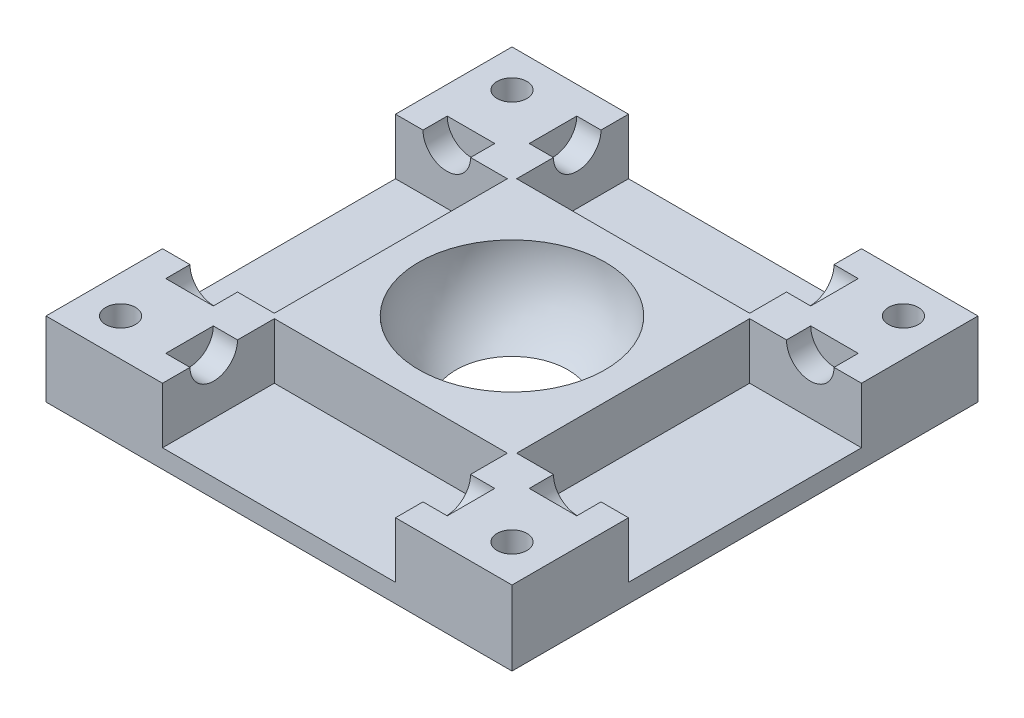
SolidWorks part; units mm, degrees
ref_plane "前视基准面" through (0, 0, 0) normal (0, 0, 1) x (1, 0, 0)
ref_plane "上视基准面" through (0, 0, 0) normal (0, 1, 0) x (1, 0, 0)
ref_plane "右视基准面" through (0, 0, 0) normal (1, 0, 0) x (0, 0, -1)
sketch "草图1" plane through (0, 0, 0) normal (0, 1, 0) x (1, 0, 0)
  line L1 (-25, -25) -> (25, -25)
  line L2 (-25, -25) -> (-25, 25)
  line L3 (-25, 25) -> (25, 25)
  line L4 (25, -25) -> (25, 25)
  line L5 (-25, -25) -> (25, 25) construction
  line L6 (-25, 25) -> (25, -25) construction
  point P0 (0, 0)
  dimension "D1" = 50
  dimension "D2" = 50
extrude "凸台-拉伸1" add sketch "草图1" along normal blind 16
sketch "草图2" plane through (0, 0, 0) normal (0, 0, 1) x (1, 0, 0)
  line L0 (0, 16) -> (0, 0) construction
  line L2 (0, 18) -> (0, -2)
  line L3 (-25, 8) -> (25, 8) construction
  line L4 (-25, 16) -> (-25, 0) construction
  line L5 (25, 16) -> (25, 0) construction
  circle A0 centre (0, 8) radius 10 construction
  arc A1 (0, 18) -> (0, -2) centre (0, 8) cw
  dimension "D1" = 20
revolve "切除-旋转1" cut sketch "草图2" angle 360 about L0
sketch "草图3" plane through (0, 16, 0) normal (0, 1, 0) x (1, 0, 0)
  line L0 (-25, 25) -> (-25, -25) construction
  line L1 (-21, -21) -> (21, -21) construction
  line L2 (-21, -21) -> (-21, 21) construction
  line L3 (-21, 21) -> (21, 21) construction
  line L4 (21, -21) -> (21, 21) construction
  line L5 (-21, -21) -> (21, 21) construction
  line L6 (-21, 21) -> (21, -21) construction
  line L7 (25, 25) -> (-25, 25) construction
  circle A0 centre (-21, 21) radius 1.6
  circle A1 centre (21, 21) radius 1.6
  circle A2 centre (21, -21) radius 1.6
  circle A3 centre (-21, -21) radius 1.6
  point P0 (0, 0)
  point P20 (0, 0)
  dimension "D3" = 3.2
  dimension "D1" = 4
  dimension "D2" = 4
  dimension "D4" = 4
extrude "切除-拉伸1" cut sketch "草图3" against normal through all
sketch "草图4" plane through (0, 16, 0) normal (0, 1, 0) x (1, 0, 0)
  circle A0 centre (-21, 21) radius 3
  dimension "D1" = 6
extrude "切除-拉伸2" [suppressed] cut sketch "草图4" against normal blind 3
sketch "草图5" plane through (0, 0, 0) normal (0, 0, 1) x (1, 0, 0)
  line L0 (0, 16) -> (0, 0) construction
  line L1 (-25, 16) -> (25, 16) construction
pattern_circular "阵列(圆周)1" [suppressed] count 4 over 360 about axis through (0, 16, 0) along (0, -1, 0)
ref_plane "基准面1" through (0, 8, 0) normal (0, 1, 0) x (1, 0, 0)
mirror "镜向1" [suppressed] about plane through (0, 8, 0) normal (0, 1, 0)
sketch "草图6" plane through (0, 0, 25) normal (0, 0, 1) x (1, 0, 0)
  line L0 (0, 16) -> (0, 0) construction
  line L1 (-12.5, 2) -> (12.5, 2)
  line L2 (-12.5, 2) -> (-12.5, 14)
  line L3 (-12.5, 14) -> (12.5, 14)
  line L4 (12.5, 2) -> (12.5, 14)
  line L5 (-12.5, 2) -> (12.5, 14) construction
  line L6 (-12.5, 14) -> (12.5, 2) construction
  point P0 (0, 8)
  dimension "D1" = 25
  dimension "D2" = 12
extrude "切除-拉伸3" cut sketch "草图6" against normal blind 12
sketch "草图7" plane through (0, 0, 0) normal (1, 0, 0) x (0, 0, -1)
  line L0 (-25, 8) -> (25, 8) construction
  line L1 (-25, 16) -> (-25, 0) construction
  line L2 (25, 16) -> (25, 0) construction
  line L3 (0, 16) -> (0, 0) construction
  line L4 (-25, 16) -> (25, 16) construction
  circle A0 centre (-19.5, 8) radius 2.55
  dimension "D1" = 5.1
  dimension "D2" = 5.5
extrude "切除-拉伸4" cut sketch "草图7" against normal blind 15.1 and the other way blind 15.1
pattern_circular "阵列(圆周)2" count 4 over 360 about axis through (0, 0, 0) along (0, 1, 0) of "切除-拉伸4", "切除-拉伸3"
sketch "草图8" plane through (0, 16, 0) normal (0, 1, 0) x (1, 0, 0)
  line L1 (-25, -25) -> (25, -25)
  line L2 (-25, -25) -> (-25, 25)
  line L3 (-25, 25) -> (25, 25)
  line L4 (25, -25) -> (25, 25)
  line L5 (-25, -25) -> (25, 25) construction
  line L6 (-25, 25) -> (25, -25) construction
  point P0 (0, 0)
extrude "切除-拉伸5" cut sketch "草图8" against normal blind 8
